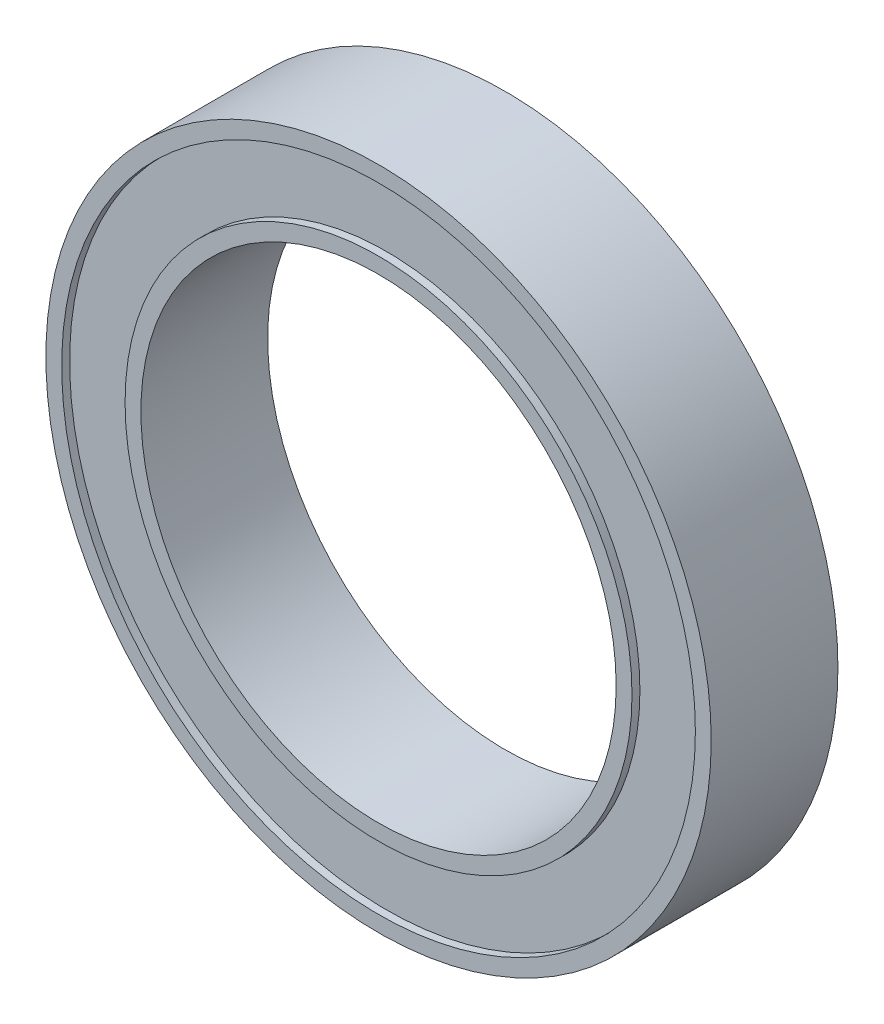
SolidWorks part; units mm, degrees
ref_plane "Front Plane" through (0, 0, 0) normal (0, 0, 1) x (1, 0, 0)
ref_plane "Top Plane" through (0, 0, 0) normal (0, 1, 0) x (1, 0, 0)
ref_plane "Right Plane" through (0, 0, 0) normal (1, 0, 0) x (0, 0, -1)
sketch "Sketch2" plane through (0, 0, 0) normal (0, 0, 1) x (1, 0, 0)
  circle A0 centre (0, 0) radius 10.5
  circle A1 centre (0, 0) radius 10
  circle A2 centre (0, 0) radius 7.5
  circle A3 centre (0, 0) radius 8
  dimension "D1" = 0.5
  dimension "D2" = 0.5
extrude "Boss-Extrude2" add sketch "Sketch2" along normal blind 4 contours A0 A1 | A3 A2
sketch "Sketch1" plane through (0, 0, 0) normal (0, 0, 1) x (1, 0, 0)
  circle A0 centre (0, 0) radius 10.5
  circle A1 centre (0, 0) radius 7.5
  dimension "D1" = 15
  dimension "D2" = 21
extrude "Boss-Extrude3" add sketch "Sketch1" along normal blind 3.5 from offset 0.25 contours A0 A1
